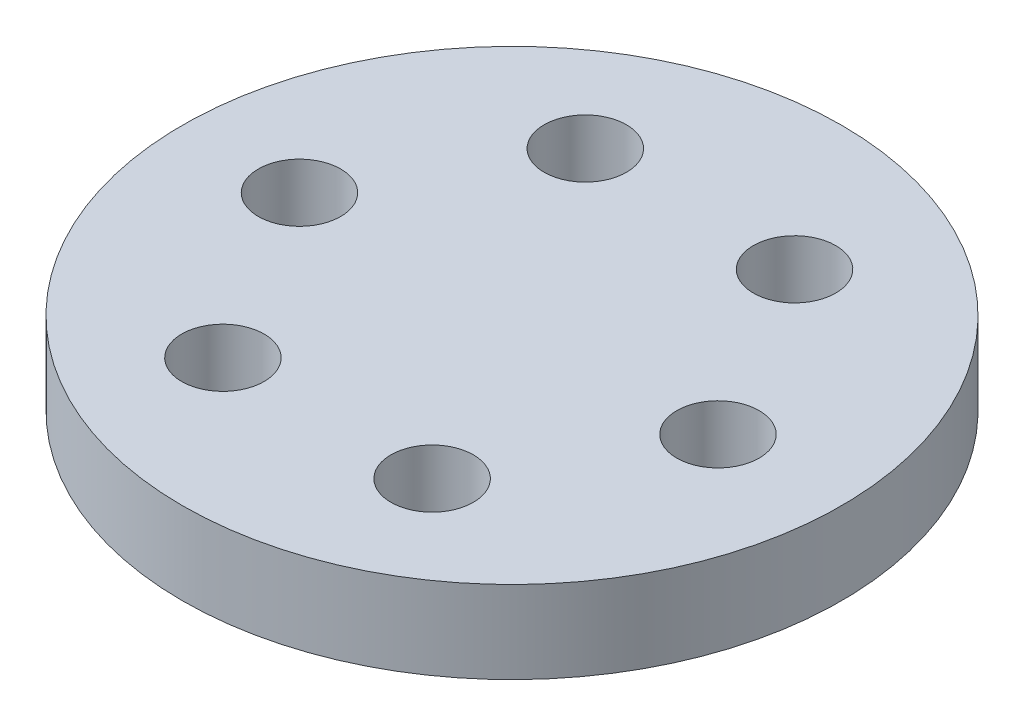
SolidWorks part; units mm, degrees
ref_plane "Front Plane" through (0, 0, 0) normal (0, 0, 1) x (1, 0, 0)
ref_plane "Top Plane" through (0, 0, 0) normal (0, 1, 0) x (1, 0, 0)
ref_plane "Right Plane" through (0, 0, 0) normal (1, 0, 0) x (0, 0, -1)
sketch "Sketch1" plane through (0, 0, 0) normal (0, 1, 0) x (1, 0, 0)
  circle A0 centre (0, 0) radius 40
extrude "Boss-Extrude1" add sketch "Sketch1" along normal blind 10
sketch "Sketch2" plane through (0, 10, 0) normal (0, 1, 0) x (1, 0, 0)
  circle A0 centre (25, 0) radius 5
extrude "Cut-Extrude1" cut sketch "Sketch2" against normal through all
pattern_circular "CirPattern1" count 6 every 60 about axis through (-0.3968, 0, 0) along (0, 1, 0) of "Cut-Extrude1"
